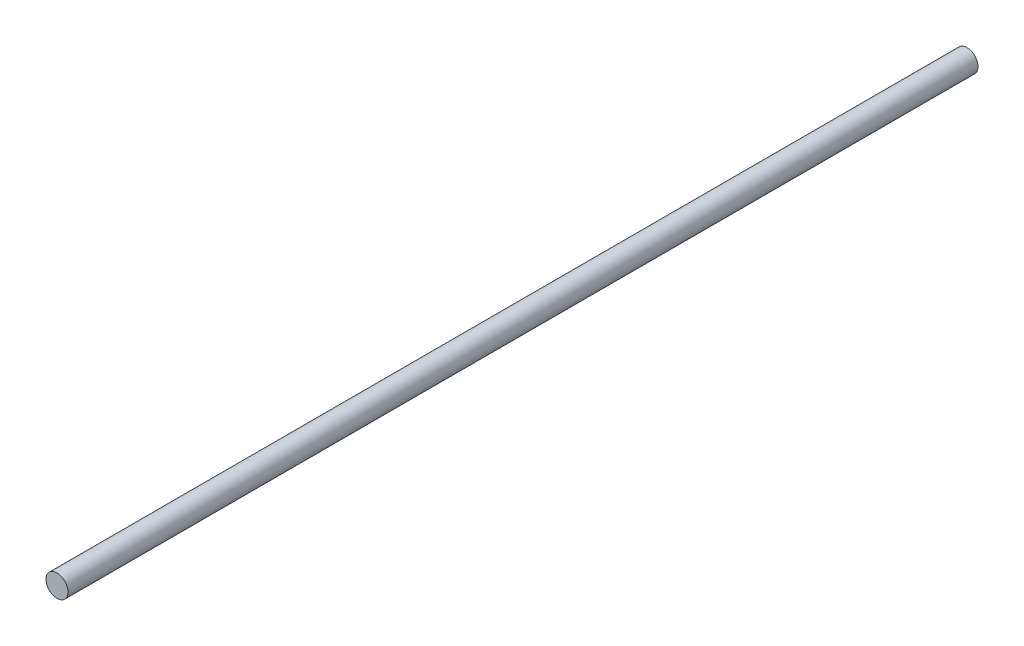
SolidWorks part; units mm, degrees
material "Nickel"
ref_plane "Front Plane" through (0, 0, 0) normal (0, 0, 1) x (1, 0, 0)
ref_plane "Top Plane" through (0, 0, 0) normal (0, 1, 0) x (1, 0, 0)
ref_plane "Right Plane" through (0, 0, 0) normal (1, 0, 0) x (0, 0, -1)
sketch "Sketch1" plane through (0, 0, 0) normal (0, 0, 1) x (1, 0, 0)
  circle A0 centre (-5.9871, 4.9645) radius 4
  dimension "D1" = 8
extrude "Boss-Extrude1" add sketch "Sketch1" along normal blind 330
